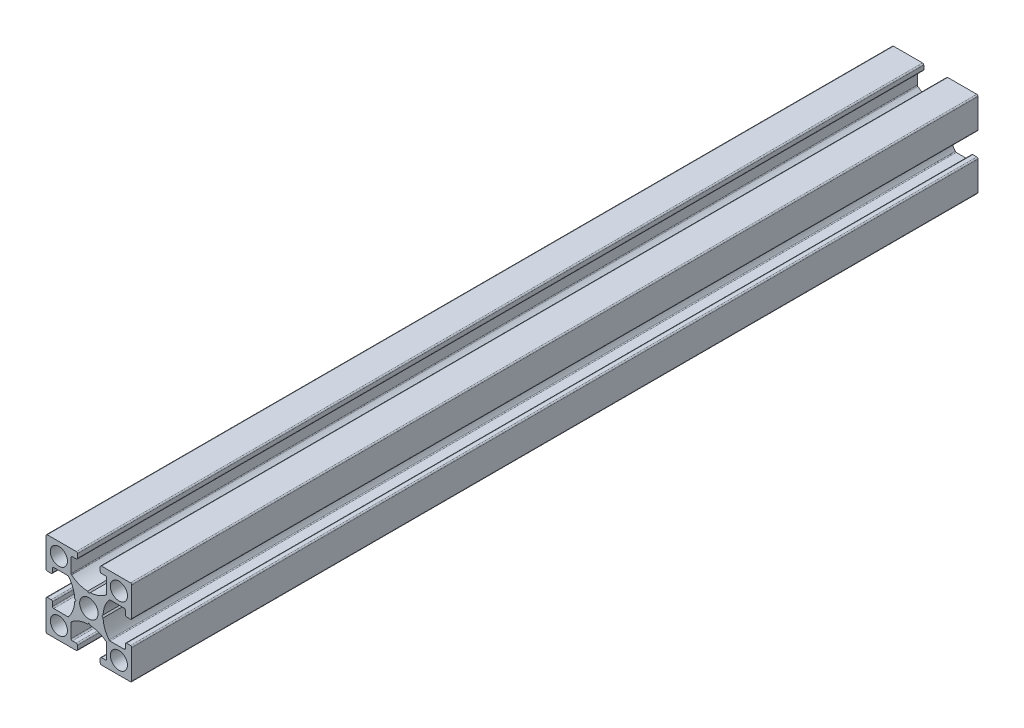
SolidWorks part; units mm, degrees
ref_plane "정면" through (0, 0, 0) normal (0, 0, 1) x (1, 0, 0)
ref_plane "윗면" through (0, 0, 0) normal (0, 1, 0) x (1, 0, 0)
ref_plane "우측면" through (0, 0, 0) normal (1, 0, 0) x (0, 0, -1)
sketch "Model" plane through (0, 0, 0) normal (0, 0, 1) x (1, 0, 0)
  line L0 (2307.7639, 1192.1343) -> (2307.7639, 1195.3915)
  line L1 (2307.4639, 1195.6915) -> (2306.5639, 1195.6915)
  line L2 (2306.2639, 1195.9915) -> (2306.2639, 1196.8915)
  line L3 (2306.5639, 1197.1915) -> (2313.3139, 1197.1915)
  line L4 (2313.6139, 1196.8915) -> (2313.6139, 1190.1415)
  line L5 (2313.3139, 1189.8415) -> (2312.4139, 1189.8415)
  line L6 (2312.1139, 1190.1415) -> (2312.1139, 1191.0415)
  line L7 (2311.8139, 1191.3415) -> (2308.5567, 1191.3415)
  line L8 (2306.9212, 1187.4988) -> (2306.6139, 1187.1915)
  line L9 (2306.6139, 1187.1915) -> (2306.9212, 1186.8843)
  line L10 (2308.5567, 1183.0415) -> (2311.8139, 1183.0415)
  line L11 (2312.1139, 1183.3415) -> (2312.1139, 1184.2415)
  line L12 (2312.4139, 1184.5415) -> (2313.3139, 1184.5415)
  line L13 (2313.6139, 1184.2415) -> (2313.6139, 1177.4915)
  line L14 (2313.3139, 1177.1915) -> (2306.5639, 1177.1915)
  line L15 (2306.2639, 1177.4915) -> (2306.2639, 1178.3915)
  line L16 (2306.5639, 1178.6915) -> (2307.4639, 1178.6915)
  line L17 (2307.7639, 1178.9915) -> (2307.7639, 1182.2488)
  line L18 (2303.9212, 1183.8843) -> (2303.6139, 1184.1915)
  line L19 (2303.6139, 1184.1915) -> (2303.3066, 1183.8843)
  line L20 (2299.4639, 1182.2488) -> (2299.4639, 1178.9915)
  line L21 (2299.7639, 1178.6915) -> (2300.6639, 1178.6915)
  line L22 (2300.9639, 1178.3915) -> (2300.9639, 1177.4915)
  line L23 (2300.6639, 1177.1915) -> (2293.9139, 1177.1915)
  line L24 (2293.6139, 1177.4915) -> (2293.6139, 1184.2415)
  line L25 (2293.9139, 1184.5415) -> (2294.8139, 1184.5415)
  line L26 (2295.1139, 1184.2415) -> (2295.1139, 1183.3415)
  line L27 (2295.4139, 1183.0415) -> (2298.6712, 1183.0415)
  line L28 (2300.3066, 1186.8843) -> (2300.6139, 1187.1915)
  line L29 (2300.6139, 1187.1915) -> (2300.3066, 1187.4988)
  line L30 (2298.6712, 1191.3415) -> (2295.4139, 1191.3415)
  line L31 (2295.1139, 1191.0415) -> (2295.1139, 1190.1415)
  line L32 (2294.8139, 1189.8415) -> (2293.9139, 1189.8415)
  line L33 (2293.6139, 1190.1415) -> (2293.6139, 1196.8915)
  line L34 (2293.9139, 1197.1915) -> (2300.6639, 1197.1915)
  line L35 (2300.9639, 1196.8915) -> (2300.9639, 1195.9915)
  line L36 (2300.6639, 1195.6915) -> (2299.7639, 1195.6915)
  line L37 (2299.4639, 1195.3915) -> (2299.4639, 1192.1343)
  line L38 (2303.3066, 1190.4988) -> (2303.6139, 1190.1915)
  line L39 (2303.6139, 1190.1915) -> (2303.9212, 1190.4988)
  circle A0 centre (2303.6139, 1187.1915) radius 2.15
  circle A1 centre (2296.6139, 1194.1915) radius 2
  circle A2 centre (2296.6139, 1180.1915) radius 2
  circle A3 centre (2310.6139, 1194.1915) radius 2
  circle A4 centre (2310.6139, 1180.1915) radius 2
  arc A5 (2307.7639, 1195.3915) -> (2307.4639, 1195.6915) centre (2307.4639, 1195.3915) ccw
  arc A6 (2306.2639, 1195.9915) -> (2306.5639, 1195.6915) centre (2306.5639, 1195.9915) ccw
  arc A7 (2306.5639, 1197.1915) -> (2306.2639, 1196.8915) centre (2306.5639, 1196.8915) ccw
  arc A8 (2313.6139, 1196.8915) -> (2313.3139, 1197.1915) centre (2313.3139, 1196.8915) ccw
  arc A9 (2313.3139, 1189.8415) -> (2313.6139, 1190.1415) centre (2313.3139, 1190.1415) ccw
  arc A10 (2312.1139, 1190.1415) -> (2312.4139, 1189.8415) centre (2312.4139, 1190.1415) ccw
  arc A11 (2312.1139, 1191.0415) -> (2311.8139, 1191.3415) centre (2311.8139, 1191.0415) ccw
  arc A12 (2308.5567, 1191.3415) -> (2308.3217, 1191.2281) centre (2308.5567, 1191.0415) ccw
  arc A13 (2308.3217, 1191.2281) -> (2306.9212, 1187.4988) centre (2313.4048, 1187.1915) ccw
  arc A14 (2306.9212, 1186.8843) -> (2308.3217, 1183.155) centre (2313.4048, 1187.1915) ccw
  arc A15 (2308.3217, 1183.155) -> (2308.5567, 1183.0415) centre (2308.5567, 1183.3415) ccw
  arc A16 (2311.8139, 1183.0415) -> (2312.1139, 1183.3415) centre (2311.8139, 1183.3415) ccw
  arc A17 (2312.4139, 1184.5415) -> (2312.1139, 1184.2415) centre (2312.4139, 1184.2415) ccw
  arc A18 (2313.6139, 1184.2415) -> (2313.3139, 1184.5415) centre (2313.3139, 1184.2415) ccw
  arc A19 (2313.3139, 1177.1915) -> (2313.6139, 1177.4915) centre (2313.3139, 1177.4915) ccw
  arc A20 (2306.2639, 1177.4915) -> (2306.5639, 1177.1915) centre (2306.5639, 1177.4915) ccw
  arc A21 (2306.5639, 1178.6915) -> (2306.2639, 1178.3915) centre (2306.5639, 1178.3915) ccw
  arc A22 (2307.4639, 1178.6915) -> (2307.7639, 1178.9915) centre (2307.4639, 1178.9915) ccw
  arc A23 (2307.7639, 1182.2488) -> (2307.6505, 1182.4837) centre (2307.4639, 1182.2488) ccw
  arc A24 (2307.6505, 1182.4837) -> (2303.9212, 1183.8843) centre (2303.6139, 1177.4007) ccw
  arc A25 (2303.3066, 1183.8843) -> (2299.5774, 1182.4837) centre (2303.6139, 1177.4007) ccw
  arc A26 (2299.5774, 1182.4837) -> (2299.4639, 1182.2488) centre (2299.7639, 1182.2488) ccw
  arc A27 (2299.4639, 1178.9915) -> (2299.7639, 1178.6915) centre (2299.7639, 1178.9915) ccw
  arc A28 (2300.9639, 1178.3915) -> (2300.6639, 1178.6915) centre (2300.6639, 1178.3915) ccw
  arc A29 (2300.6639, 1177.1915) -> (2300.9639, 1177.4915) centre (2300.6639, 1177.4915) ccw
  arc A30 (2293.6139, 1177.4915) -> (2293.9139, 1177.1915) centre (2293.9139, 1177.4915) ccw
  arc A31 (2293.9139, 1184.5415) -> (2293.6139, 1184.2415) centre (2293.9139, 1184.2415) ccw
  arc A32 (2295.1139, 1184.2415) -> (2294.8139, 1184.5415) centre (2294.8139, 1184.2415) ccw
  arc A33 (2295.1139, 1183.3415) -> (2295.4139, 1183.0415) centre (2295.4139, 1183.3415) ccw
  arc A34 (2298.6712, 1183.0415) -> (2298.9061, 1183.155) centre (2298.6712, 1183.3415) ccw
  arc A35 (2298.9061, 1183.155) -> (2300.3066, 1186.8843) centre (2293.8231, 1187.1915) ccw
  arc A36 (2300.3066, 1187.4988) -> (2298.9061, 1191.2281) centre (2293.8231, 1187.1915) ccw
  arc A37 (2298.9061, 1191.2281) -> (2298.6712, 1191.3415) centre (2298.6712, 1191.0415) ccw
  arc A38 (2295.4139, 1191.3415) -> (2295.1139, 1191.0415) centre (2295.4139, 1191.0415) ccw
  arc A39 (2294.8139, 1189.8415) -> (2295.1139, 1190.1415) centre (2294.8139, 1190.1415) ccw
  arc A40 (2293.6139, 1190.1415) -> (2293.9139, 1189.8415) centre (2293.9139, 1190.1415) ccw
  arc A41 (2293.9139, 1197.1915) -> (2293.6139, 1196.8915) centre (2293.9139, 1196.8915) ccw
  arc A42 (2300.9639, 1196.8915) -> (2300.6639, 1197.1915) centre (2300.6639, 1196.8915) ccw
  arc A43 (2300.6639, 1195.6915) -> (2300.9639, 1195.9915) centre (2300.6639, 1195.9915) ccw
  arc A44 (2299.7639, 1195.6915) -> (2299.4639, 1195.3915) centre (2299.7639, 1195.3915) ccw
  arc A45 (2299.4639, 1192.1343) -> (2299.5774, 1191.8994) centre (2299.7639, 1192.1343) ccw
  arc A46 (2299.5774, 1191.8994) -> (2303.3066, 1190.4988) centre (2303.6139, 1196.9824) ccw
  arc A47 (2303.9212, 1190.4988) -> (2307.6505, 1191.8994) centre (2303.6139, 1196.9824) ccw
  arc A48 (2307.6505, 1191.8994) -> (2307.7639, 1192.1343) centre (2307.4639, 1192.1343) ccw
extrude "보스-돌출1" add sketch "Model" along normal blind 197.38
sketch "스케치2" plane through (2313.6139, 0, 0) normal (1, 0, 0) x (0, 0, -1)
  line L0 (-9.9994, 1197.1915) -> (-9.9994, 847.1915) construction
  line L1 (-177.38, 1197.1915) -> (-177.38, 847.1915) construction
  circle A0 centre (-9.9994, 1187.1915) radius 2.5
  circle A1 centre (-177.38, 1187.1915) radius 2.5
extrude "컷-돌출3" cut sketch "스케치2" against normal through all
